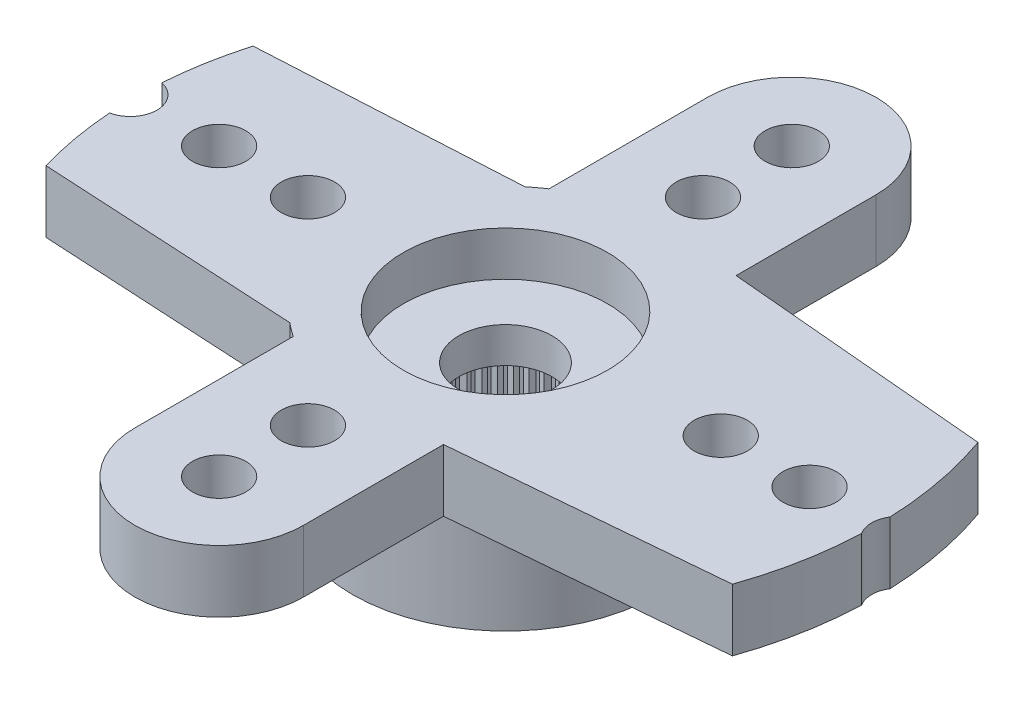
SolidWorks part; units mm, degrees
material "PVC Rígido"
ref_plane "Plano frontal" through (0, 0, 0) normal (0, 0, 1) x (1, 0, 0)
ref_plane "Plano superior" through (0, 0, 0) normal (0, 1, 0) x (1, 0, 0)
ref_plane "Plano direito" through (0, 0, 0) normal (1, 0, 0) x (0, 0, -1)
sketch "Esboço1" plane through (0, 0, 0) normal (0, 1, 0) x (1, 0, 0)
  line L0 (0, 0) -> (-14.05, 0) construction
  line L1 (-14.1591, 1.997) -> (-2.2091, 2.65)
  line L2 (-2.2091, -2.65) -> (-14.1591, -1.997)
  arc A0 (-2.2091, -2.65) -> (-2.2091, 2.65) centre (0, 0) ccw
  arc A1 (-14.1591, 1.997) -> (-14.1591, -1.997) centre (-14.05, 0) ccw
  dimension "D1" = 6.9
  dimension "D2" = 4
  dimension "D3" = 19.5
  dimension "D4" = 5.3
extrude "Ressalto-extrusão1" add sketch "Esboço1" against normal blind 1.4
sketch "Esboço2" plane through (0, -1.4, 0) normal (0, -1, 0) x (1, 0, 0)
  arc A0 (-2.2091, -2.65) -> (-2.2091, 2.65) centre (0, 0) ccw construction
  circle A1 centre (0, 0) radius 3.45
extrude "Ressalto-extrusão2" add sketch "Esboço2" along normal offset from surface (2.4 mm away) 3.8 up to face at (-7.242, 0, 0)
hole_wizard "Furo1" positions "Esboço9" profile "Esboço10" legacy end condition through all
sketch "Esboço9" plane through (0, 0, 0) normal (0, 1, 0) x (1, 0, 0)
  line L1 (-14.45, 0) -> (0, 0) construction
  arc A2 (-14.1591, 1.997) -> (-14.1591, -1.997) centre (-14.05, 0) ccw construction
  point P0 (-14.45, 0)
  point P19 (-16.05, 0)
  dimension "D1" = 1.6
sketch "Esboço10" plane through (-14.45, 0, 0) normal (1, 0, 0) x (0, 0, 1)
  line L0 (0, 0) -> (0, 3.8)
  line L1 (0, 3.8) -> (0.6, 3.8)
  line L2 (0.6, 3.8) -> (0.6, 0)
  line L3 (0.6, 0) -> (0, 0)
  line L4 (0, 110) -> (0, -10) construction
  dimension "Diameter" = 1.2
  dimension "Depth" = 3.8
pattern_linear "Padrão linear1" count 6 spacing 2 along (1, 0, 0) of "Furo1"
sketch "Esboço12" plane through (0, 0, 0) normal (0, 1, 0) x (1, 0, 0)
  line L0 (0.3041, 3.4366) -> (16.6263, 1.9922)
  line L1 (16.6263, -1.9922) -> (0.3041, -3.4366)
  arc A0 (-2.2091, -2.65) -> (-2.2091, 2.65) centre (0, 0) ccw construction
  arc A1 (0.3041, -3.4366) -> (0.3041, 3.4366) centre (0, 0) ccw
  arc A2 (16.6263, 1.9922) -> (16.6263, -1.9922) centre (16.45, 0) cw
  arc A3 (-14.1591, 1.997) -> (-14.1591, -1.997) centre (-14.05, 0) ccw construction
  dimension "D1" = 2
  dimension "D2" = 34.5
extrude "Ressalto-extrusão3" add sketch "Esboço12" against normal up to surface (1.4 mm away) up to face at (-12.45, -1.4, 0.6)
hole_wizard "Furo2" positions "Esboço13" profile "Esboço14" legacy end condition through all
sketch "Esboço13" plane through (0, 0, 0) normal (0, 1, 0) x (1, 0, 0)
  line L0 (0, 0) -> (16.85, 0) construction
  arc A0 (16.6263, -1.9922) -> (16.6263, 1.9922) centre (16.45, 0) ccw construction
  point P0 (16.85, 0)
  point P6 (18.45, 0)
  dimension "D1" = 1.6
sketch "Esboço14" plane through (16.85, 0, 0) normal (1, 0, 0) x (0, 0, 1)
  line L0 (0, 0) -> (0, 3.8)
  line L1 (0, 3.8) -> (0.6, 3.8)
  line L2 (0.6, 3.8) -> (0.6, 0)
  line L3 (0.6, 0) -> (0, 0)
  line L4 (0, 110) -> (0, -10) construction
  dimension "Diameter" = 1.2
  dimension "Depth" = 3.8
pattern_linear "Padrão linear2" count 7 spacing 2 along (-1, 0, 0) of "Furo2"
sketch "Esboço16" plane through (0, 0, 0) normal (0, 1, 0) x (1, 0, 0)
  line L0 (0, -6.45) -> (0, 6.45) construction
  line L1 (-1.9, -6.45) -> (-1.9, 6.45)
  line L2 (1.9, -6.45) -> (1.9, 6.45)
  arc A0 (-1.9, -6.45) -> (1.9, -6.45) centre (0, -6.45) ccw
  arc A1 (1.9, 6.45) -> (-1.9, 6.45) centre (0, 6.45) ccw
  point P2 (0, 0)
  dimension "D2" = 16.7
  dimension "D1" = 3.8
extrude "Ressalto-extrusão4" add sketch "Esboço16" against normal up to surface (1.4 mm away) up to face at (14.85, -1.4, 0.6)
hole_wizard "Furo3" positions "Esboço17" profile "Esboço18" legacy end condition through all
sketch "Esboço17" plane through (0, 0, 0) normal (0, 1, 0) x (1, 0, 0)
  point P0 (0, -6.45)
sketch "Esboço18" plane through (0, 0, 6.45) normal (1, 0, 0) x (0, 0, 1)
  line L0 (0, 0) -> (0, 3.8)
  line L1 (0, 3.8) -> (0.6, 3.8)
  line L2 (0.6, 3.8) -> (0.6, 0)
  line L3 (0.6, 0) -> (0, 0)
  line L4 (0, 110) -> (0, -10) construction
  dimension "Diameter" = 1.2
  dimension "Depth" = 3.8
pattern_linear "Padrão linear3" count 2 spacing 2 along (0, 0, -1) of "Furo3"
pattern_circular "PadrãoCircular1" count 2 over 360 about axis through (0, 0, 0) along (0, 1, 0) of "Padrão linear3", "Furo3"
hole_wizard "Furo4" positions "Esboço3" profile "Esboço4" legacy
sketch "Esboço3" plane through (0, -3.8, 0) normal (0, -1, 0) x (-1, 0, 0)
  point P0 (0, 0)
sketch "Esboço4" plane through (0, -3.8, 0) normal (1, 0, 0) x (0, 0, -1)
  line L0 (0, 0) -> (0, 2)
  line L1 (0, 2) -> (2.475, 2)
  line L2 (2.475, 2) -> (2.475, 0)
  line L3 (2.475, 0) -> (0, 0)
  line L4 (0, 110) -> (0, -10) construction
  dimension "Diameter" = 4.95
  dimension "Depth" = 2
hole_wizard "Furo5" positions "Esboço5" profile "Esboço6" legacy
sketch "Esboço5" plane through (0, 0, 0) normal (0, 1, 0) x (1, 0, 0)
  point P0 (0, 0)
sketch "Esboço6" plane through (0, 0, 0) normal (1, 0, 0) x (0, 0, 1)
  line L0 (0, 0) -> (0, 1)
  line L1 (0, 1) -> (2.3, 1)
  line L2 (2.3, 1) -> (2.3, 0)
  line L3 (2.3, 0) -> (0, 0)
  line L4 (0, 110) -> (0, -10) construction
  dimension "Diameter" = 4.6
  dimension "Depth" = 1
hole_wizard "Furo6" positions "Esboço7" profile "Esboço8" legacy end condition through all
sketch "Esboço7" plane through (0, 0, 0) normal (0, 1, 0) x (1, 0, 0)
  point P0 (0, 0)
sketch "Esboço8" plane through (0, 0, 0) normal (1, 0, 0) x (0, 0, 1)
  line L0 (0, 0) -> (0, 3.8)
  line L1 (0, 3.8) -> (1.05, 3.8)
  line L2 (1.05, 3.8) -> (1.05, 0)
  line L3 (1.05, 0) -> (0, 0)
  line L4 (0, 110) -> (0, -10) construction
  dimension "Diameter" = 2.1
  dimension "Depth" = 3.8
sketch "Esboço11" plane through (0, -3.8, 0) normal (0, -1, 0) x (1, 0, 0)
  line L0 (-0.0981, 2.4731) -> (0, 2.375)
  line L1 (0, 2.375) -> (0.0981, 2.4731)
  line L2 (0, 0) -> (0, 2.475) construction
  circle A0 centre (0, 0) radius 2.375 construction
  circle A1 centre (0, 0) radius 2.475
  arc A2 (0.0981, 2.4731) -> (-0.0981, 2.4731) centre (0, 0) ccw
  dimension "D3" = 4.75
  dimension "D2" = 0.1
  dimension "D1" = 0
extrude "Ressalto-extrusão5" add sketch "Esboço11" against normal up to surface (2 mm away) up to face at (0, -1.8, 1.05)
pattern_circular "PadrãoCircular2" count 60 over 360 about axis through (0, 0, 0) along (0, 1, 0) of "Ressalto-extrusão5"
sketch "Sketch1" plane through (0, 0, 0) normal (0, 1, 0) x (1, 0, 0)
  circle A0 centre (0, 0) radius 8.35
  circle A1 centre (0, 0) radius 18.45
extrude "Cut-Extrude1" cut sketch "Sketch1" against normal blind 10
